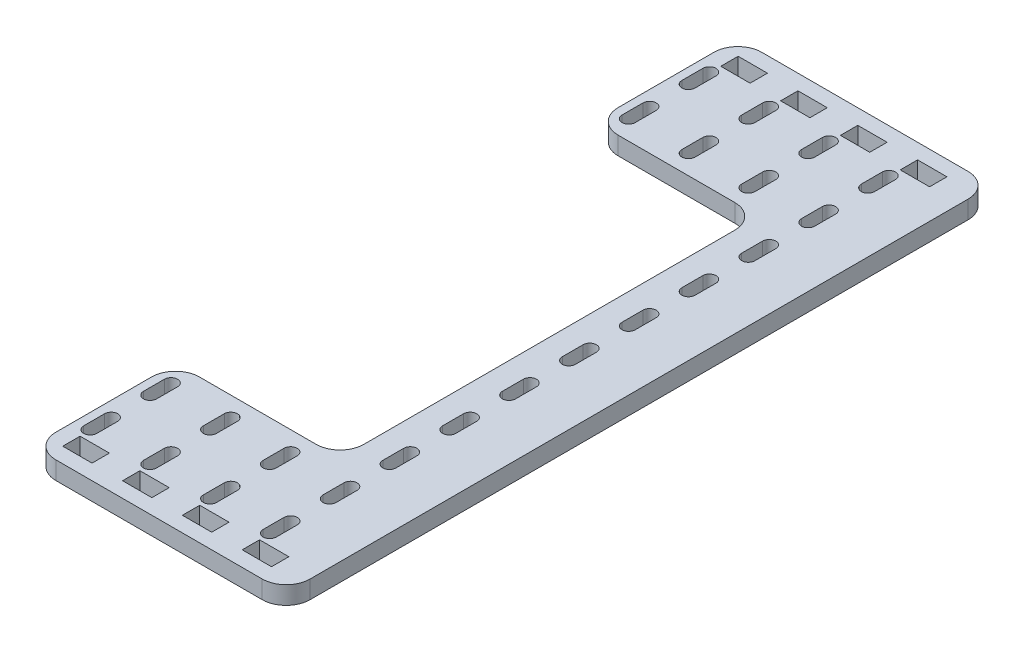
SolidWorks part; units mm, degrees
ref_plane "Front Plane" through (0, 0, 0) normal (0, 0, 1) x (1, 0, 0)
ref_plane "Top Plane" through (0, 0, 0) normal (0, 1, 0) x (1, 0, 0)
ref_plane "Right Plane" through (0, 0, 0) normal (1, 0, 0) x (0, 0, -1)
sketch "Sketch1" plane through (0, 0, 0) normal (0, 1, 0) x (1, 0, 0)
  line L0 (-43.1232, 117.3768) -> (41.8768, 117.3768)
  line L1 (-43.1232, 117.3768) -> (-43.1232, -118.6232)
  line L2 (-43.1232, -118.6232) -> (41.8768, -118.6232)
  line L3 (41.8768, 117.3768) -> (41.8768, -118.6232)
  line L4 (-43.1232, 117.3768) -> (41.8768, -118.6232) construction
  line L5 (-43.1232, -118.6232) -> (41.8768, 117.3768) construction
  point P4 (-0.6232, -0.6232)
extrude "Boss-Extrude1" add sketch "Sketch1" along normal blind 6
sketch "Sketch2" plane through (0, 6, 0) normal (0, 1, 0) x (1, 0, 0)
  line L0 (41.8768, -113.5232) -> (31.8768, -113.5232) construction
  line L1 (41.8768, -118.6232) -> (41.8768, 117.3768) construction
  line L2 (-43.1232, -118.6232) -> (41.8768, -118.6232) construction
  line L3 (11.8768, -107.7232) -> (2.0768, -107.7232)
  line L4 (31.8768, -113.5232) -> (22.0768, -113.5232)
  line L5 (31.8768, -113.5232) -> (31.8768, -107.7232)
  line L6 (31.8768, -107.7232) -> (22.0768, -107.7232)
  line L7 (22.0768, -113.5232) -> (22.0768, -107.7232)
  line L8 (31.8768, -113.5232) -> (22.0768, -107.7232) construction
  line L9 (31.8768, -107.7232) -> (22.0768, -113.5232) construction
  line L10 (2.0768, -113.5232) -> (2.0768, -107.7232)
  line L11 (11.8768, -113.5232) -> (2.0768, -113.5232)
  line L12 (11.8768, -113.5232) -> (11.8768, -107.7232)
  line L13 (-8.1232, -107.7232) -> (-17.9232, -107.7232)
  line L14 (-17.9232, -113.5232) -> (-17.9232, -107.7232)
  line L15 (-8.1232, -113.5232) -> (-17.9232, -113.5232)
  line L16 (-8.1232, -113.5232) -> (-8.1232, -107.7232)
  line L17 (-28.1232, -107.7232) -> (-37.9232, -107.7232)
  line L18 (-37.9232, -113.5232) -> (-37.9232, -107.7232)
  line L19 (-28.1232, -113.5232) -> (-37.9232, -113.5232)
  line L20 (-28.1232, -113.5232) -> (-28.1232, -107.7232)
  point P9 (26.9768, -110.6232)
  dimension "D1" = 10
  dimension "D2" = 5.1
  dimension "D3" = 9.8
  dimension "D4" = 5.8
  dimension "D5" = 4
extrude "Cut-Extrude1" cut sketch "Sketch2" against normal blind 6
ref_plane "Plane1" through (0, 0, 0.6232) normal (0, 0, 1) x (1, 0, 0)
mirror "Mirror2" about plane through (0, 0, 0.6232) normal (0, 0, 1) of "Cut-Extrude1"
sketch "Sketch4" plane through (0, 6, 0) normal (0, 1, 0) x (1, 0, 0)
  line L0 (21.8768, 99.3768) -> (21.8768, 79.3768) construction
  line L1 (21.8768, 99.3768) -> (24.0768, 99.3768) construction
  line L2 (21.8768, 99.3768) -> (19.6768, 99.3768) construction
  line L3 (24.0768, 95.8768) -> (24.0768, 102.8768)
  line L4 (-43.1232, 117.3768) -> (-43.1232, -118.6232) construction
  line L5 (-43.1232, -118.6232) -> (41.8768, -118.6232) construction
  line L6 (41.8768, -118.6232) -> (41.8768, 117.3768) construction
  line L7 (41.8768, 117.3768) -> (-43.1232, 117.3768) construction
  line L8 (19.6768, 95.8768) -> (19.6768, 102.8768)
  line L9 (21.8768, 95.8768) -> (21.8768, 102.8768) construction
  line L10 (4.0768, 95.8768) -> (4.0768, 102.8768)
  line L11 (-0.3232, 95.8768) -> (-0.3232, 102.8768)
  line L12 (-15.9232, 95.8768) -> (-15.9232, 102.8768)
  line L13 (-43.1232, 117.3768) -> (-43.1232, -118.6232) construction
  line L14 (41.8768, 117.3768) -> (-43.1232, 117.3768) construction
  line L15 (-20.3232, 95.8768) -> (-20.3232, 102.8768)
  line L16 (-35.9232, 95.8768) -> (-35.9232, 102.8768)
  line L17 (-40.3232, 95.8768) -> (-40.3232, 102.8768)
  line L18 (4.0768, 75.8768) -> (4.0768, 82.8768)
  line L19 (-0.3232, 75.8768) -> (-0.3232, 82.8768)
  line L20 (-15.9232, 75.8768) -> (-15.9232, 82.8768)
  line L21 (-20.3232, 75.8768) -> (-20.3232, 82.8768)
  line L22 (-35.9232, 75.8768) -> (-35.9232, 82.8768)
  line L23 (-40.3232, 75.8768) -> (-40.3232, 82.8768)
  line L24 (4.0768, 55.8768) -> (4.0768, 62.8768)
  line L25 (-0.3232, 55.8768) -> (-0.3232, 62.8768)
  line L26 (-15.9232, 55.8768) -> (-15.9232, 62.8768)
  line L27 (-20.3232, 55.8768) -> (-20.3232, 62.8768)
  line L28 (-35.9232, 55.8768) -> (-35.9232, 62.8768)
  line L29 (-40.3232, 55.8768) -> (-40.3232, 62.8768)
  line L30 (4.0768, 35.8768) -> (4.0768, 42.8768)
  line L31 (-0.3232, 35.8768) -> (-0.3232, 42.8768)
  line L32 (-15.9232, 35.8768) -> (-15.9232, 42.8768)
  line L33 (-20.3232, 35.8768) -> (-20.3232, 42.8768)
  line L34 (-35.9232, 35.8768) -> (-35.9232, 42.8768)
  line L35 (-40.3232, 35.8768) -> (-40.3232, 42.8768)
  line L36 (4.0768, 15.8768) -> (4.0768, 22.8768)
  line L37 (-0.3232, 15.8768) -> (-0.3232, 22.8768)
  line L38 (-15.9232, 15.8768) -> (-15.9232, 22.8768)
  line L39 (-20.3232, 15.8768) -> (-20.3232, 22.8768)
  line L40 (-35.9232, 15.8768) -> (-35.9232, 22.8768)
  line L41 (-40.3232, 15.8768) -> (-40.3232, 22.8768)
  line L42 (4.0768, -4.1232) -> (4.0768, 2.8768)
  line L43 (-0.3232, -4.1232) -> (-0.3232, 2.8768)
  line L44 (-15.9232, -4.1232) -> (-15.9232, 2.8768)
  line L45 (-20.3232, -4.1232) -> (-20.3232, 2.8768)
  line L46 (-35.9232, -4.1232) -> (-35.9232, 2.8768)
  line L47 (-40.3232, -4.1232) -> (-40.3232, 2.8768)
  line L48 (4.0768, -24.1232) -> (4.0768, -17.1232)
  line L49 (-0.3232, -24.1232) -> (-0.3232, -17.1232)
  line L50 (-15.9232, -24.1232) -> (-15.9232, -17.1232)
  line L51 (-20.3232, -24.1232) -> (-20.3232, -17.1232)
  line L52 (-35.9232, -24.1232) -> (-35.9232, -17.1232)
  line L53 (-40.3232, -24.1232) -> (-40.3232, -17.1232)
  line L54 (4.0768, -44.1232) -> (4.0768, -37.1232)
  line L55 (-0.3232, -44.1232) -> (-0.3232, -37.1232)
  line L56 (-15.9232, -44.1232) -> (-15.9232, -37.1232)
  line L57 (-20.3232, -44.1232) -> (-20.3232, -37.1232)
  line L58 (-35.9232, -44.1232) -> (-35.9232, -37.1232)
  line L59 (-40.3232, -44.1232) -> (-40.3232, -37.1232)
  line L60 (4.0768, -64.1232) -> (4.0768, -57.1232)
  line L61 (-0.3232, -64.1232) -> (-0.3232, -57.1232)
  line L62 (-15.9232, -64.1232) -> (-15.9232, -57.1232)
  line L63 (-20.3232, -64.1232) -> (-20.3232, -57.1232)
  line L64 (-35.9232, -64.1232) -> (-35.9232, -57.1232)
  line L65 (-40.3232, -64.1232) -> (-40.3232, -57.1232)
  line L66 (4.0768, -84.1232) -> (4.0768, -77.1232)
  line L67 (-0.3232, -84.1232) -> (-0.3232, -77.1232)
  line L68 (-15.9232, -84.1232) -> (-15.9232, -77.1232)
  line L69 (-20.3232, -84.1232) -> (-20.3232, -77.1232)
  line L70 (-35.9232, -84.1232) -> (-35.9232, -77.1232)
  line L71 (-40.3232, -84.1232) -> (-40.3232, -77.1232)
  line L72 (4.0768, -104.1232) -> (4.0768, -97.1232)
  line L73 (-0.3232, -104.1232) -> (-0.3232, -97.1232)
  line L74 (-15.9232, -104.1232) -> (-15.9232, -97.1232)
  line L75 (-20.3232, -104.1232) -> (-20.3232, -97.1232)
  line L76 (-35.9232, -104.1232) -> (-35.9232, -97.1232)
  line L77 (-40.3232, -104.1232) -> (-40.3232, -97.1232)
  line L78 (24.0768, 75.8768) -> (24.0768, 82.8768)
  line L79 (19.6768, 75.8768) -> (19.6768, 82.8768)
  line L80 (24.0768, 55.8768) -> (24.0768, 62.8768)
  line L81 (19.6768, 55.8768) -> (19.6768, 62.8768)
  line L82 (24.0768, 35.8768) -> (24.0768, 42.8768)
  line L83 (19.6768, 35.8768) -> (19.6768, 42.8768)
  line L84 (24.0768, 15.8768) -> (24.0768, 22.8768)
  line L85 (19.6768, 15.8768) -> (19.6768, 22.8768)
  line L86 (24.0768, -4.1232) -> (24.0768, 2.8768)
  line L87 (19.6768, -4.1232) -> (19.6768, 2.8768)
  line L88 (24.0768, -24.1232) -> (24.0768, -17.1232)
  line L89 (19.6768, -24.1232) -> (19.6768, -17.1232)
  line L90 (24.0768, -44.1232) -> (24.0768, -37.1232)
  line L91 (19.6768, -44.1232) -> (19.6768, -37.1232)
  line L92 (24.0768, -64.1232) -> (24.0768, -57.1232)
  line L93 (19.6768, -64.1232) -> (19.6768, -57.1232)
  line L94 (24.0768, -84.1232) -> (24.0768, -77.1232)
  line L95 (19.6768, -84.1232) -> (19.6768, -77.1232)
  line L96 (24.0768, -104.1232) -> (24.0768, -97.1232)
  line L97 (19.6768, -104.1232) -> (19.6768, -97.1232)
  arc A2 (19.6768, 102.8768) -> (24.0768, 102.8768) centre (21.8768, 102.8768) cw
  arc A3 (19.6768, 95.8768) -> (24.0768, 95.8768) centre (21.8768, 95.8768) ccw
  arc A4 (-0.3232, 95.8768) -> (4.0768, 95.8768) centre (1.8768, 95.8768) ccw
  arc A5 (-0.3232, 102.8768) -> (4.0768, 102.8768) centre (1.8768, 102.8768) cw
  arc A6 (-20.3232, 95.8768) -> (-15.9232, 95.8768) centre (-18.1232, 95.8768) ccw
  arc A7 (-20.3232, 102.8768) -> (-15.9232, 102.8768) centre (-18.1232, 102.8768) cw
  arc A8 (-40.3232, 95.8768) -> (-35.9232, 95.8768) centre (-38.1232, 95.8768) ccw
  arc A9 (-40.3232, 102.8768) -> (-35.9232, 102.8768) centre (-38.1232, 102.8768) cw
  arc A10 (-0.3232, 75.8768) -> (4.0768, 75.8768) centre (1.8768, 75.8768) ccw
  arc A11 (-0.3232, 82.8768) -> (4.0768, 82.8768) centre (1.8768, 82.8768) cw
  arc A12 (-20.3232, 75.8768) -> (-15.9232, 75.8768) centre (-18.1232, 75.8768) ccw
  arc A13 (-20.3232, 82.8768) -> (-15.9232, 82.8768) centre (-18.1232, 82.8768) cw
  arc A14 (-40.3232, 75.8768) -> (-35.9232, 75.8768) centre (-38.1232, 75.8768) ccw
  arc A15 (-40.3232, 82.8768) -> (-35.9232, 82.8768) centre (-38.1232, 82.8768) cw
  arc A16 (-0.3232, 55.8768) -> (4.0768, 55.8768) centre (1.8768, 55.8768) ccw
  arc A17 (-0.3232, 62.8768) -> (4.0768, 62.8768) centre (1.8768, 62.8768) cw
  arc A18 (-20.3232, 55.8768) -> (-15.9232, 55.8768) centre (-18.1232, 55.8768) ccw
  arc A19 (-20.3232, 62.8768) -> (-15.9232, 62.8768) centre (-18.1232, 62.8768) cw
  arc A20 (-40.3232, 55.8768) -> (-35.9232, 55.8768) centre (-38.1232, 55.8768) ccw
  arc A21 (-40.3232, 62.8768) -> (-35.9232, 62.8768) centre (-38.1232, 62.8768) cw
  arc A22 (-0.3232, 35.8768) -> (4.0768, 35.8768) centre (1.8768, 35.8768) ccw
  arc A23 (-0.3232, 42.8768) -> (4.0768, 42.8768) centre (1.8768, 42.8768) cw
  arc A24 (-20.3232, 35.8768) -> (-15.9232, 35.8768) centre (-18.1232, 35.8768) ccw
  arc A25 (-20.3232, 42.8768) -> (-15.9232, 42.8768) centre (-18.1232, 42.8768) cw
  arc A26 (-40.3232, 35.8768) -> (-35.9232, 35.8768) centre (-38.1232, 35.8768) ccw
  arc A27 (-40.3232, 42.8768) -> (-35.9232, 42.8768) centre (-38.1232, 42.8768) cw
  arc A28 (-0.3232, 15.8768) -> (4.0768, 15.8768) centre (1.8768, 15.8768) ccw
  arc A29 (-0.3232, 22.8768) -> (4.0768, 22.8768) centre (1.8768, 22.8768) cw
  arc A30 (-20.3232, 15.8768) -> (-15.9232, 15.8768) centre (-18.1232, 15.8768) ccw
  arc A31 (-20.3232, 22.8768) -> (-15.9232, 22.8768) centre (-18.1232, 22.8768) cw
  arc A32 (-40.3232, 15.8768) -> (-35.9232, 15.8768) centre (-38.1232, 15.8768) ccw
  arc A33 (-40.3232, 22.8768) -> (-35.9232, 22.8768) centre (-38.1232, 22.8768) cw
  arc A34 (-0.3232, -4.1232) -> (4.0768, -4.1232) centre (1.8768, -4.1232) ccw
  arc A35 (-0.3232, 2.8768) -> (4.0768, 2.8768) centre (1.8768, 2.8768) cw
  arc A36 (-20.3232, -4.1232) -> (-15.9232, -4.1232) centre (-18.1232, -4.1232) ccw
  arc A37 (-20.3232, 2.8768) -> (-15.9232, 2.8768) centre (-18.1232, 2.8768) cw
  arc A38 (-40.3232, -4.1232) -> (-35.9232, -4.1232) centre (-38.1232, -4.1232) ccw
  arc A39 (-40.3232, 2.8768) -> (-35.9232, 2.8768) centre (-38.1232, 2.8768) cw
  arc A40 (-0.3232, -24.1232) -> (4.0768, -24.1232) centre (1.8768, -24.1232) ccw
  arc A41 (-0.3232, -17.1232) -> (4.0768, -17.1232) centre (1.8768, -17.1232) cw
  arc A42 (-20.3232, -24.1232) -> (-15.9232, -24.1232) centre (-18.1232, -24.1232) ccw
  arc A43 (-20.3232, -17.1232) -> (-15.9232, -17.1232) centre (-18.1232, -17.1232) cw
  arc A44 (-40.3232, -24.1232) -> (-35.9232, -24.1232) centre (-38.1232, -24.1232) ccw
  arc A45 (-40.3232, -17.1232) -> (-35.9232, -17.1232) centre (-38.1232, -17.1232) cw
  arc A46 (-0.3232, -44.1232) -> (4.0768, -44.1232) centre (1.8768, -44.1232) ccw
  arc A47 (-0.3232, -37.1232) -> (4.0768, -37.1232) centre (1.8768, -37.1232) cw
  arc A48 (-20.3232, -44.1232) -> (-15.9232, -44.1232) centre (-18.1232, -44.1232) ccw
  arc A49 (-20.3232, -37.1232) -> (-15.9232, -37.1232) centre (-18.1232, -37.1232) cw
  arc A50 (-40.3232, -44.1232) -> (-35.9232, -44.1232) centre (-38.1232, -44.1232) ccw
  arc A51 (-40.3232, -37.1232) -> (-35.9232, -37.1232) centre (-38.1232, -37.1232) cw
  arc A52 (-0.3232, -64.1232) -> (4.0768, -64.1232) centre (1.8768, -64.1232) ccw
  arc A53 (-0.3232, -57.1232) -> (4.0768, -57.1232) centre (1.8768, -57.1232) cw
  arc A54 (-20.3232, -64.1232) -> (-15.9232, -64.1232) centre (-18.1232, -64.1232) ccw
  arc A55 (-20.3232, -57.1232) -> (-15.9232, -57.1232) centre (-18.1232, -57.1232) cw
  arc A56 (-40.3232, -64.1232) -> (-35.9232, -64.1232) centre (-38.1232, -64.1232) ccw
  arc A57 (-40.3232, -57.1232) -> (-35.9232, -57.1232) centre (-38.1232, -57.1232) cw
  arc A58 (-0.3232, -84.1232) -> (4.0768, -84.1232) centre (1.8768, -84.1232) ccw
  arc A59 (-0.3232, -77.1232) -> (4.0768, -77.1232) centre (1.8768, -77.1232) cw
  arc A60 (-20.3232, -84.1232) -> (-15.9232, -84.1232) centre (-18.1232, -84.1232) ccw
  arc A61 (-20.3232, -77.1232) -> (-15.9232, -77.1232) centre (-18.1232, -77.1232) cw
  arc A62 (-40.3232, -84.1232) -> (-35.9232, -84.1232) centre (-38.1232, -84.1232) ccw
  arc A63 (-40.3232, -77.1232) -> (-35.9232, -77.1232) centre (-38.1232, -77.1232) cw
  arc A64 (-0.3232, -104.1232) -> (4.0768, -104.1232) centre (1.8768, -104.1232) ccw
  arc A65 (-0.3232, -97.1232) -> (4.0768, -97.1232) centre (1.8768, -97.1232) cw
  arc A66 (-20.3232, -104.1232) -> (-15.9232, -104.1232) centre (-18.1232, -104.1232) ccw
  arc A67 (-20.3232, -97.1232) -> (-15.9232, -97.1232) centre (-18.1232, -97.1232) cw
  arc A68 (-40.3232, -104.1232) -> (-35.9232, -104.1232) centre (-38.1232, -104.1232) ccw
  arc A69 (-40.3232, -97.1232) -> (-35.9232, -97.1232) centre (-38.1232, -97.1232) cw
  arc A70 (19.6768, 75.8768) -> (24.0768, 75.8768) centre (21.8768, 75.8768) ccw
  arc A71 (19.6768, 82.8768) -> (24.0768, 82.8768) centre (21.8768, 82.8768) cw
  arc A72 (19.6768, 55.8768) -> (24.0768, 55.8768) centre (21.8768, 55.8768) ccw
  arc A73 (19.6768, 62.8768) -> (24.0768, 62.8768) centre (21.8768, 62.8768) cw
  arc A74 (19.6768, 35.8768) -> (24.0768, 35.8768) centre (21.8768, 35.8768) ccw
  arc A75 (19.6768, 42.8768) -> (24.0768, 42.8768) centre (21.8768, 42.8768) cw
  arc A76 (19.6768, 15.8768) -> (24.0768, 15.8768) centre (21.8768, 15.8768) ccw
  arc A77 (19.6768, 22.8768) -> (24.0768, 22.8768) centre (21.8768, 22.8768) cw
  arc A78 (19.6768, -4.1232) -> (24.0768, -4.1232) centre (21.8768, -4.1232) ccw
  arc A79 (19.6768, 2.8768) -> (24.0768, 2.8768) centre (21.8768, 2.8768) cw
  arc A80 (19.6768, -24.1232) -> (24.0768, -24.1232) centre (21.8768, -24.1232) ccw
  arc A81 (19.6768, -17.1232) -> (24.0768, -17.1232) centre (21.8768, -17.1232) cw
  arc A82 (19.6768, -44.1232) -> (24.0768, -44.1232) centre (21.8768, -44.1232) ccw
  arc A83 (19.6768, -37.1232) -> (24.0768, -37.1232) centre (21.8768, -37.1232) cw
  arc A84 (19.6768, -64.1232) -> (24.0768, -64.1232) centre (21.8768, -64.1232) ccw
  arc A85 (19.6768, -57.1232) -> (24.0768, -57.1232) centre (21.8768, -57.1232) cw
  arc A86 (19.6768, -84.1232) -> (24.0768, -84.1232) centre (21.8768, -84.1232) ccw
  arc A87 (19.6768, -77.1232) -> (24.0768, -77.1232) centre (21.8768, -77.1232) cw
  arc A88 (19.6768, -104.1232) -> (24.0768, -104.1232) centre (21.8768, -104.1232) ccw
  arc A89 (19.6768, -97.1232) -> (24.0768, -97.1232) centre (21.8768, -97.1232) cw
  point P10 (24.0768, 99.3768)
  point P13 (19.6768, 99.3768)
  point P22 (21.8768, 99.3768)
  dimension "D7" = 17.8
  dimension "D9" = 20
  dimension "D1" = 2.2
  dimension "D2" = 2.2
  dimension "D3" = 7
  dimension "D4" = 7
  dimension "D5" = 85
  dimension "D6" = 236
  dimension "D8" = 18
  dimension "D10" = 4
  dimension "D11" = 11
extrude "Cut-Extrude2" cut sketch "Sketch4" against normal through all contours L8 A3 L3 A2 | A71 L79 A70 L78 | A73 L81 A72 L80 | A75 L83 A74 L82 | A23 L31 A22 L30 | A17 L25 A16 L24 | A11 L19 A10 L18 | A5 L11 A4 L10 | A13 L21 A12 L20 | A7 L15 A6 L12 | A19 L27 A18 L26 | A25 L33 A24 L32 | A31 L39 A30 L38 | A29 L37 A28 L36 | A77 L85 A76 L84 | A35 L43 A34 L42 | A37 L45 A36 L44 | A33 L41 A32 L40 | A27 L35 A26 L34 | A21 L29 A20 L28 | A15 L23 A14 L22 | A9 L17 A8 L16 | A79 L87 A78 L86 | A81 L89 A80 L88 | A83 L91 A82 L90 | A47 L55 A46 L54 | A41 L49 A40 L48 | A43 L51 A42 L50 | A49 L57 A48 L56 | A51 L59 A50 L58 | A45 L53 A44 L52 | A39 L47 A38 L46 | A89 L97 A88 L96 | A87 L95 A86 L94 | A85 L93 A84 L92 | A53 L61 A52 L60 | A59 L67 A58 L66 | A65 L73 A64 L72 | A67 L75 A66 L74 | A69 L77 A68 L76 | A63 L71 A62 L70 | A61 L69 A60 L68 | A55 L63 A54 L62 | A57 L65 A56 L64
sketch "Sketch5" plane through (0, 6, 0) normal (0, 1, 0) x (1, 0, 0)
  line L0 (-43.1232, 117.3768) -> (-43.1232, -118.6232) construction
  line L1 (-43.1232, 69.3768) -> (11.8768, 69.3768)
  line L2 (-43.1232, 69.3768) -> (-43.1232, -70.6232)
  line L3 (-43.1232, -70.6232) -> (11.8768, -70.6232)
  line L4 (11.8768, 69.3768) -> (11.8768, -70.6232)
  line L5 (-43.1232, 69.3768) -> (11.8768, -70.6232) construction
  line L6 (-43.1232, -70.6232) -> (11.8768, 69.3768) construction
  line L7 (41.8768, 117.3768) -> (-43.1232, 117.3768) construction
  line L8 (-43.1232, -118.6232) -> (41.8768, -118.6232) construction
  line L9 (19.6768, 59.3768) -> (11.8768, 59.3768) construction
  line L10 (19.6768, 55.8768) -> (19.6768, 62.8768) construction
  point P4 (-15.6232, -0.6232)
  dimension "D1" = 48
  dimension "D2" = 48
  dimension "D3" = 7.8
extrude "Cut-Extrude3" cut sketch "Sketch5" against normal through all
fillet "Fillet1" radius 8 8 edges at (41.8768, 3, -117.3768) (11.8768, 3, -69.3768) (11.8768, 3, 70.6232) (41.8768, 3, 118.6232) (-43.1232, 3, 118.6232) (-43.1232, 3, 70.6232) (-43.1232, 3, -117.3768) (-43.1232, 3, -69.3768)
